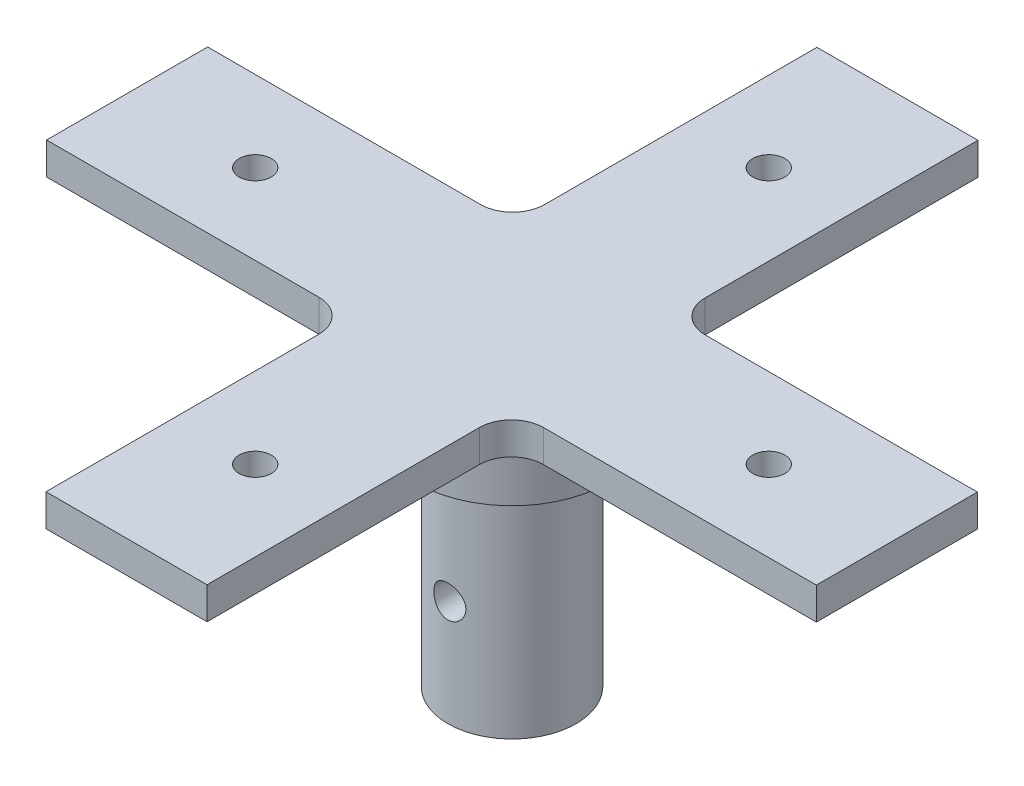
SolidWorks part; units mm, degrees
ref_plane "Front Plane" through (0, 0, 0) normal (0, 0, 1) x (1, 0, 0)
ref_plane "Top Plane" through (0, 0, 0) normal (0, 1, 0) x (1, 0, 0)
ref_plane "Right Plane" through (0, 0, 0) normal (1, 0, 0) x (0, 0, -1)
sketch "Sketch1" plane through (0, 0, 0) normal (0, 1, 0) x (1, 0, 0)
  circle A0 centre (0, 0) radius 10
extrude "Boss-Extrude1" add sketch "Sketch1" along normal blind 35
sketch "Sketch2" plane through (0, 35, 0) normal (0, 1, 0) x (1, 0, 0)
  circle A0 centre (0, 0) radius 15
extrude "Boss-Extrude2" add sketch "Sketch2" along normal blind 10
sketch "Sketch3" plane through (0, 45, 0) normal (0, 1, 0) x (1, 0, 0)
  line L0 (-60, 0) -> (-60, 12.5896)
  line L1 (12.5896, 60) -> (-12.5, 60)
  line L2 (60, -12.5896) -> (60, 12.5)
  line L3 (12.5, -60) -> (-12.5896, -60)
  line L14 (-60, 0) -> (-60, -12.5)
  line L15 (-60, -12.5) -> (-17.5881, -12.5)
  line L16 (-60, 12.5896) -> (-17.4985, 12.5896)
  line L17 (12.5896, 60) -> (12.5896, 17.4985)
  line L24 (-12.5, 60) -> (-12.5, 17.5881)
  line L25 (60, -12.5896) -> (17.4985, -12.5896)
  line L28 (60, 12.5) -> (17.5881, 12.5)
  line L29 (-12.5896, -60) -> (-12.5896, -17.4985)
  line L32 (12.5, -60) -> (12.5, -17.5881)
  line L33 (0, 60) -> (12.5896, 60) [skipped]
  line L34 (0, 60) -> (-12.5, 60) [skipped]
  line L35 (0, -60) -> (12.5, -60) [skipped]
  line L36 (0, -60) -> (-12.5896, -60) [skipped]
  line L37 (60, 0) -> (60, -12.5896) [skipped]
  line L38 (60, 0) -> (60, 12.5) [skipped]
  arc A0 (-12.5896, -17.4985) -> (-17.5881, -12.5) centre (-17.5881, -17.4985) ccw
  circle A1 centre (0, 40) radius 2.5
  circle A2 centre (40, 0) radius 2.5
  circle A3 centre (0, -40) radius 2.5
  circle A4 centre (-40, 0) radius 2.5
  arc A5 (-17.4985, 12.5896) -> (-12.5, 17.5881) centre (-17.4985, 17.5881) ccw
  arc A6 (12.5896, 17.4985) -> (17.5881, 12.5) centre (17.5881, 17.4985) ccw
  arc A7 (17.4985, -12.5896) -> (12.5, -17.5881) centre (17.4985, -17.5881) ccw
  point P24 (0, 0)
  point P38 (0, 0)
  point P61 (0, 0)
  dimension "D1" = 4
  dimension "D2" = 4
  dimension "D3" = 4
extrude "Boss-Extrude3" add sketch "Sketch3" along normal blind 5
sketch "Sketch7" plane through (0, 0, 0) normal (0, 0, 1) x (1, 0, 0)
  line L0 (0, 35) -> (0, 16.5) construction
  line L1 (-10, 35) -> (10, 35) construction
  circle A0 centre (0, 16.5) radius 2.5
extrude "Cut-Extrude1" cut sketch "Sketch7" along normal blind 50 and the other way blind 26
